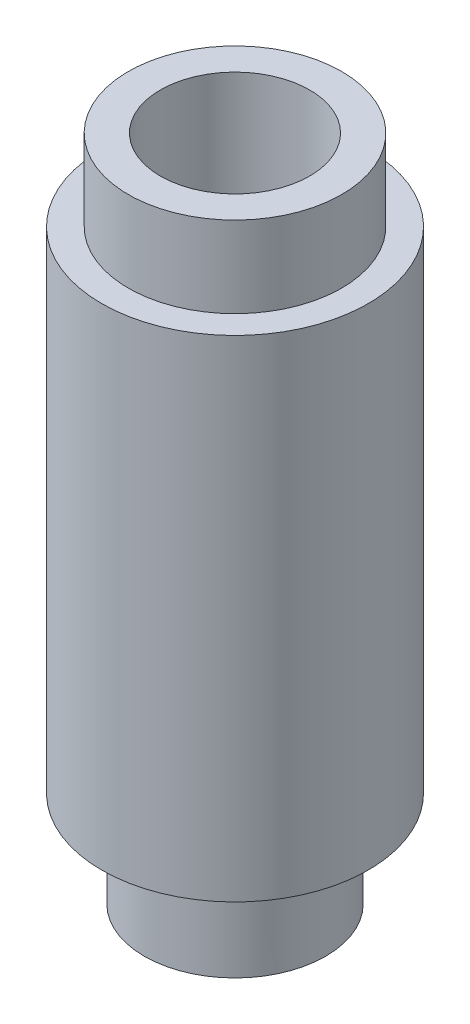
SolidWorks part; units mm, degrees
ref_plane "Plano frontal" through (0, 0, 0) normal (0, 0, 1) x (1, 0, 0)
ref_plane "Plano superior" through (0, 0, 0) normal (0, 1, 0) x (1, 0, 0)
ref_plane "Plano direito" through (0, 0, 0) normal (1, 0, 0) x (0, 0, -1)
sketch "Sketch1" plane through (0, 0, 0) normal (0, 1, 0) x (1, 0, 0)
  circle A0 centre (0, 0) radius 12.5
  dimension "D1" = 25
extrude "Boss-Extrude1" add sketch "Sketch1" along normal blind 46
sketch "Sketch2" plane through (0, 0, 0) normal (0, -1, 0) x (1, 0, 0)
  circle A0 centre (0, 0) radius 8.375
  dimension "D1" = 16.75
extrude "Boss-Extrude2" add sketch "Sketch2" along normal blind 4
sketch "Sketch3" plane through (0, 46, 0) normal (0, 1, 0) x (1, 0, 0)
  circle A0 centre (0, 0) radius 10
  dimension "D1" = 20
extrude "Boss-Extrude4" add sketch "Sketch3" along normal blind 7.6
sketch "Sketch4" plane through (0, 0, 0) normal (0, -1, 0) x (1, 0, 0)
  circle A0 centre (0, 0) radius 8.5
  dimension "D1" = 17
extrude "Boss-Extrude5" add sketch "Sketch4" along normal blind 9
sketch "Sketch5" plane through (0, 53.6, 0) normal (0, 1, 0) x (1, 0, 0)
  circle A0 centre (0, 0) radius 5
  dimension "D1" = 10
extrude "Cut-Extrude1" cut sketch "Sketch5" against normal through all
sketch "Sketch6" plane through (0, 53.6, 0) normal (0, 1, 0) x (1, 0, 0)
  circle A0 centre (0, 0) radius 7
  dimension "D1" = 14
extrude "Cut-Extrude2" cut sketch "Sketch6" against normal through all
